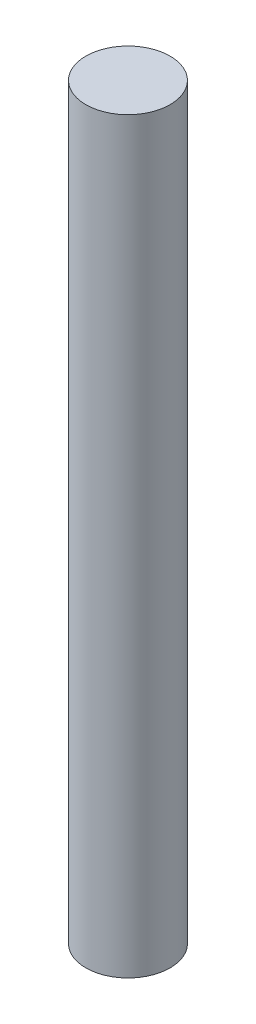
SolidWorks part; units mm, degrees
ref_plane "Front Plane" through (0, 0, 0) normal (0, 0, 1) x (1, 0, 0)
ref_plane "Top Plane" through (0, 0, 0) normal (0, 1, 0) x (1, 0, 0)
ref_plane "Right Plane" through (0, 0, 0) normal (1, 0, 0) x (0, 0, -1)
sketch "Sketch1" plane through (0, 0, 0) normal (0, 1, 0) x (1, 0, 0)
  circle A0 centre (0, 0) radius 37.465
  dimension "D1" = 74.93
extrude "Boss-Extrude1" add sketch "Sketch1" along normal blind 665.48
